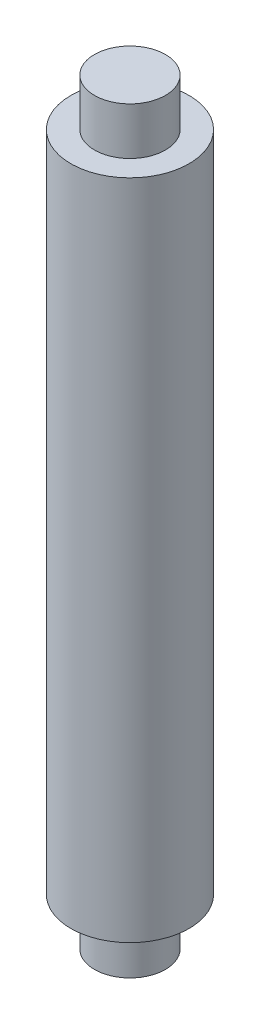
SolidWorks part; units mm, degrees
ref_plane "Front Plane" through (0, 0, 0) normal (0, 0, 1) x (1, 0, 0)
ref_plane "Top Plane" through (0, 0, 0) normal (0, 1, 0) x (1, 0, 0)
ref_plane "Right Plane" through (0, 0, 0) normal (1, 0, 0) x (0, 0, -1)
sketch "Sketch1" plane through (0, 0, 0) normal (0, 0, 1) x (1, 0, 0)
  line L0 (0, 10.8289) -> (0, -21.1711)
  line L1 (0, -21.1711) -> (-1.5, -21.1711)
  line L2 (-1.5, -21.1711) -> (-1.5, -19.1711)
  line L3 (-1.5, -19.1711) -> (-2.5, -19.1711)
  line L4 (-2.5, -19.1711) -> (-2.5, 8.8289)
  line L5 (-2.5, 8.8289) -> (-1.5, 8.8289)
  line L6 (-1.5, 8.8289) -> (-1.5, 10.8289)
  line L7 (-1.5, 10.8289) -> (0, 10.8289)
  dimension "D1" = 1.5
  dimension "D2" = 28
  dimension "D3" = 2.5
  dimension "D4" = 1.5
  dimension "D5" = 2
  dimension "D6" = 2
revolve "Revolve1" add sketch "Sketch1" angle 360 about L0
